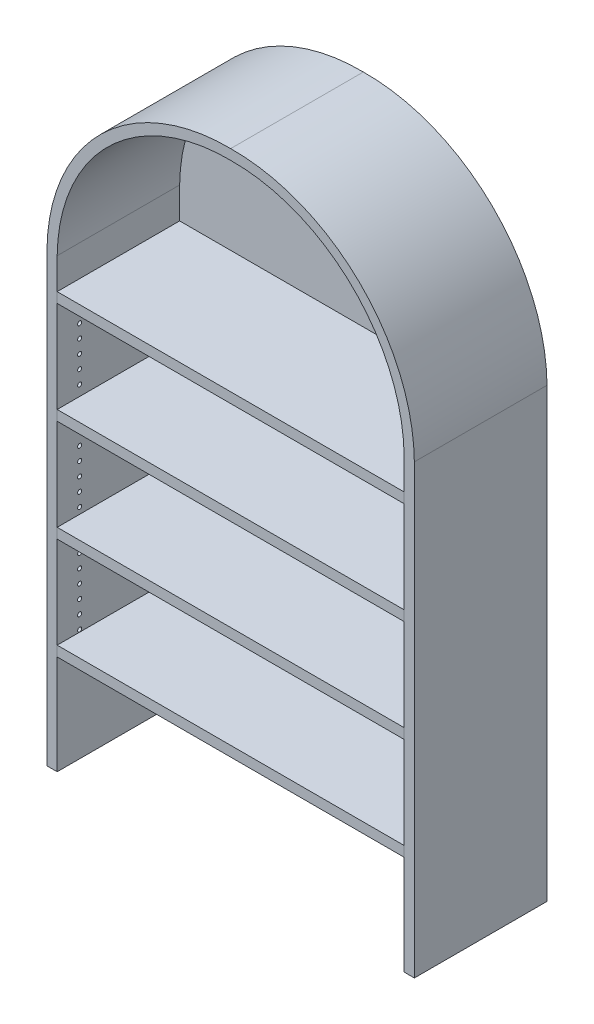
SolidWorks part; units mm, degrees
ref_plane "Front Plane" through (0, 0, 0) normal (0, 0, 1) x (1, 0, 0)
ref_plane "Top Plane" through (0, 0, 0) normal (0, 1, 0) x (1, 0, 0)
ref_plane "Right Plane" through (0, 0, 0) normal (1, 0, 0) x (0, 0, -1)
sketch "Sketch1" plane through (0, 0, 0) normal (0, 0, 1) x (1, 0, 0)
  line L0 (-457.2, 610.9892) -> (-457.2, -501.5171)
  line L1 (0, 1098.2609) -> (0, -501.5171) construction
  line L2 (-457.2, -501.5171) -> (457.2, -501.5171)
  line L3 (457.2, 610.9892) -> (457.2, -501.5171)
  arc A0 (-457.2, 610.9892) -> (0, 1057.6313) centre (-5.2789, 605.7103) cw
  arc A1 (457.2, 610.9892) -> (0, 1057.6313) centre (5.2789, 605.7103) ccw
  dimension "D1" = 457.2
extrude "Boss-Extrude1" add sketch "Sketch1" along normal blind 25.4
sketch "Sketch2" plane through (0, 0, 25.4) normal (0, 0, 1) x (1, 0, 0)
  line L0 (457.2, -501.5171) -> (457.2, 610.9892) construction
  line L2 (-457.2, 610.9892) -> (-457.2, -501.5171) construction
  line L3 (457.2, -501.5171) -> (457.2, 610.9892)
  line L5 (-457.2, 610.9892) -> (-457.2, -501.5171)
  line L6 (-431.8, 610.8387) -> (-431.8, -476.1171)
  line L8 (431.8, -476.1171) -> (431.8, 610.8387)
  line L9 (-431.8, -476.1171) -> (431.8, -476.1171) construction
  line L10 (-457.2, -501.5171) -> (457.2, -501.5171) construction
  line L11 (-431.8, -476.1171) -> (-431.8, -501.5171)
  line L12 (-457.2, -501.5171) -> (457.2, -501.5171) construction
  line L13 (-431.8, -501.5171) -> (431.8, -501.5171)
  line L14 (431.8, -501.5171) -> (431.8, -476.1171)
  line L15 (-457.2, -501.5171) -> (-431.8, -501.5171)
  line L16 (431.8, -501.5171) -> (457.2, -501.5171)
  arc A0 (457.2, 610.9892) -> (0, 1057.6313) centre (5.2789, 605.7103) ccw construction
  arc A1 (0, 1057.6313) -> (-457.2, 610.9892) centre (-5.2789, 605.7103) ccw construction
  arc A2 (457.2, 610.9892) -> (0, 1057.6313) centre (5.2789, 605.7103) ccw
  arc A3 (0, 1057.6313) -> (-457.2, 610.9892) centre (-5.2789, 605.7103) ccw
  arc A4 (0, 1032.2295) -> (-431.8, 610.8387) centre (-5.2789, 605.7103) ccw
  arc A5 (431.8, 610.8387) -> (0, 1032.2295) centre (5.2789, 605.7103) ccw
  arc M13 (0, 1057.6313) -> (-457.2, 610.9892) centre (-5.2789, 605.7103) ccw
  line M14 (-457.2, 610.9892) -> (-457.2, -501.5171)
  line M15 (-457.2, -501.5171) -> (457.2, -501.5171)
  line M16 (457.2, -501.5171) -> (457.2, 610.9892)
  arc M17 (457.2, 610.9892) -> (0, 1057.6313) centre (5.2789, 605.7103) ccw
  dimension "D1" = 25.4
extrude "Boss-Extrude2" add sketch "Sketch2" along normal blind 304.8 contours A5 L8 L14 L11 L6 A4 M15 M16 M17 M13 M14
sketch "Sketch3" plane through (0, 0, 25.4) normal (0, 0, 1) x (1, 0, 0)
  line L0 (-431.8, -254) -> (431.8, -254)
  line L1 (-431.8, 610.8387) -> (-431.8, -501.5171) construction
  line L2 (431.8, -501.5171) -> (431.8, 610.8387) construction
  line L3 (431.8, -254) -> (431.8, -228.6)
  line L4 (431.8, -228.6) -> (-431.8, -228.6)
  line L5 (-431.8, 610.8387) -> (-431.8, -501.5171) construction
  line L6 (-431.8, -228.6) -> (-431.8, -254)
  line L7 (-431.8, 0) -> (431.8, 0)
  line L8 (431.8, 0) -> (431.8, 25.4)
  line L9 (431.8, 25.4) -> (-431.8, 25.4)
  line L10 (-431.8, 25.4) -> (-431.8, 0)
  line L11 (-431.8, 279.4) -> (431.8, 279.4)
  line L12 (431.8, -501.5171) -> (431.8, 610.8387) construction
  line L13 (431.8, 254) -> (-431.8, 254)
  line L14 (-431.8, 254) -> (-431.8, 279.4)
  line L15 (431.8, 279.4) -> (431.8, 254)
  line L16 (-431.8, 508) -> (431.8, 508)
  line L17 (431.8, 508) -> (431.8, 533.4)
  line L18 (431.8, 533.4) -> (-431.8, 533.4)
  line L19 (-431.8, 533.4) -> (-431.8, 508)
  dimension "D1" = 25.4
  dimension "D2" = 25.4
  dimension "D3" = 25.4
  dimension "D4" = 228.6
  dimension "D5" = 228.6
  dimension "D6" = 25.4
  dimension "D7" = 228.6
extrude "Boss-Extrude3" add sketch "Sketch3" along normal blind 304.8 separate body
sketch "Sketch4" plane through (-431.8, 0, 0) normal (1, 0, 0) x (0, 0, -1)
  line L0 (-165.1, -501.5171) -> (-165.1, 689.0159) construction
  line L1 (-330.2, -501.5171) -> (0, -501.5171) construction
  circle A0 centre (-274.2547, 503.3415) radius 5.08
  circle A1 centre (-274.2547, 470.3215) radius 5.08
  circle A2 centre (-274.2547, 437.3015) radius 5.08
  circle A3 centre (-274.2547, 404.2815) radius 5.08
  circle A4 centre (-274.2547, 371.2615) radius 5.08
  circle A5 centre (-274.2547, 338.2415) radius 5.08
  circle A6 centre (-274.2547, 305.2215) radius 5.08
  circle A7 centre (-274.2547, 272.2015) radius 5.08
  circle A8 centre (-274.2547, 239.1815) radius 5.08
  circle A9 centre (-274.2547, 206.1615) radius 5.08
  circle A10 centre (-274.2547, 173.1415) radius 5.08
  circle A11 centre (-274.2547, 140.1215) radius 5.08
  circle A12 centre (-274.2547, 107.1015) radius 5.08
  circle A13 centre (-274.2547, 74.0815) radius 5.08
  circle A14 centre (-274.2547, 41.0615) radius 5.08
  circle A15 centre (-274.2547, 8.0415) radius 5.08
  circle A16 centre (-274.2547, -24.9785) radius 5.08
  circle A17 centre (-274.2547, -57.9985) radius 5.08
  circle A18 centre (-274.2547, -91.0185) radius 5.08
  circle A19 centre (-274.2547, -124.0385) radius 5.08
  circle A20 centre (-274.2547, -157.0585) radius 5.08
  circle A21 centre (-274.2547, -190.0785) radius 5.08
  circle A22 centre (-274.2547, -223.0985) radius 5.08
  circle A23 centre (-274.2547, -256.1185) radius 5.08
  circle A24 centre (-55.9453, 404.2815) radius 5.08
  circle A25 centre (-55.9453, 437.3015) radius 5.08
  circle A26 centre (-55.9453, 470.3215) radius 5.08
  circle A27 centre (-55.9453, 503.3415) radius 5.08
  circle A28 centre (-55.9453, 272.2015) radius 5.08
  circle A29 centre (-55.9453, 305.2215) radius 5.08
  circle A30 centre (-55.9453, 338.2415) radius 5.08
  circle A31 centre (-55.9453, 371.2615) radius 5.08
  circle A32 centre (-55.9453, 239.1815) radius 5.08
  circle A33 centre (-55.9453, 206.1615) radius 5.08
  circle A34 centre (-55.9453, 173.1415) radius 5.08
  circle A35 centre (-55.9453, 140.1215) radius 5.08
  circle A36 centre (-55.9453, 107.1015) radius 5.08
  circle A37 centre (-55.9453, 74.0815) radius 5.08
  circle A38 centre (-55.9453, 41.0615) radius 5.08
  circle A39 centre (-55.9453, 8.0415) radius 5.08
  circle A40 centre (-55.9453, -24.9785) radius 5.08
  circle A41 centre (-55.9453, -57.9985) radius 5.08
  circle A42 centre (-55.9453, -124.0385) radius 5.08
  circle A43 centre (-55.9453, -91.0185) radius 5.08
  circle A44 centre (-55.9453, -157.0585) radius 5.08
  circle A45 centre (-55.9453, -190.0785) radius 5.08
  circle A46 centre (-55.9453, -223.0985) radius 5.08
  circle A47 centre (-55.9453, -256.1185) radius 5.08
  dimension "D1" = 24
extrude "Cut-Extrude1" cut sketch "Sketch4" against normal blind 7.62 and the other way blind 873.76
sketch "Sketch5" plane through (0, 0, 25.4) normal (0, 0, 1) x (1, 0, 0)
  line L0 (431.8, -501.5171) -> (431.8, 610.8387) construction
  line L1 (-431.8, -501.5171) -> (431.8, -501.5171)
  line L2 (-431.8, -501.5171) -> (-431.8, -455.1127)
  line L3 (-431.8, -455.1127) -> (431.8, -455.1127)
  line L4 (431.8, -501.5171) -> (431.8, -455.1127)
extrude "Boss-Extrude4" add sketch "Sketch5" along normal blind 25.4
